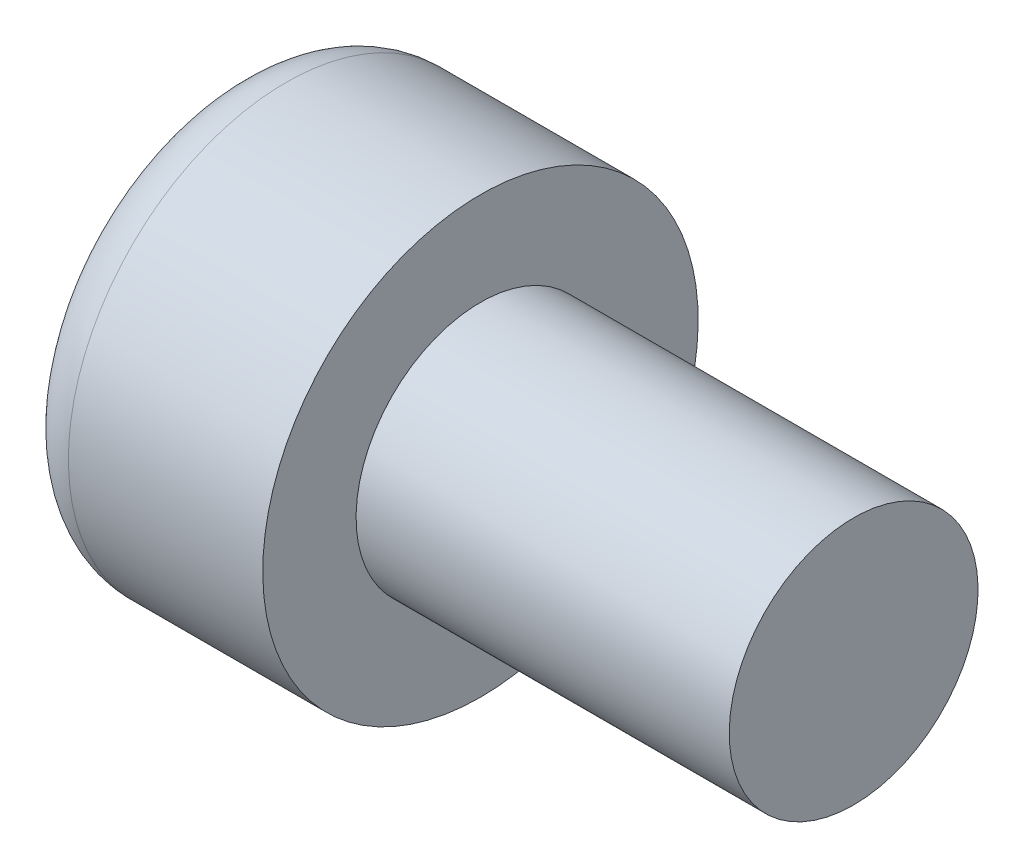
SolidWorks part; units mm, degrees
material "Plain Carbon Steel"
ref_plane "Front Plane" through (0, 0, 0) normal (0, 0, 1) x (1, 0, 0)
ref_plane "Top Plane" through (0, 0, 0) normal (0, 1, 0) x (1, 0, 0)
ref_plane "Right Plane" through (0, 0, 0) normal (1, 0, 0) x (0, 0, -1)
sketch "Sketch1" plane through (0, 0, 0) normal (0, 0, 1) x (1, 0, 0)
  line L0 (0, 0) -> (0, 2.625)
  line L1 (0.875, 3.5) -> (4, 3.5)
  line L2 (4, 3.5) -> (4, 2)
  line L3 (4, 2) -> (10, 2)
  line L4 (10, 2) -> (10, 0)
  line L5 (10, 0) -> (0, 0) construction
  line L6 (0.875, 2.625) -> (0.875, 1.75) construction
  line L7 (0.875, 1.75) -> (0.875, 0.875) construction
  line L8 (0.875, 0.875) -> (0.875, 0) construction
  line L9 (0.875, 3.5) -> (0.875, 2.625) construction
  line L10 (0, 0) -> (10, 0)
  arc A0 (0, 2.625) -> (0.875, 3.5) centre (0.875, 2.625) cw
  dimension "D1" = 4
  dimension "D2" = 7
  dimension "D3" = 4
  dimension "D4" = 6
revolve "Revolve1" add sketch "Sketch1" angle 360 about L10
sketch "Sketch2" plane through (0, 0, 0) normal (-1, 0, 0) x (0, 0, 1)
  line L1 (0, 1.7321) -> (-1.5, 0.866)
  line L2 (-1.5, 0.866) -> (-1.5, -0.866)
  line L3 (-1.5, -0.866) -> (0, -1.7321)
  line L4 (0, -1.7321) -> (1.5, -0.866)
  line L5 (1.5, -0.866) -> (1.5, 0.866)
  line L6 (1.5, 0.866) -> (0, 1.7321)
  circle A0 centre (0, 0) radius 1.5 construction
  dimension "D1" = 3
extrude "Cut-Extrude1" cut sketch "Sketch2" against normal blind 2
